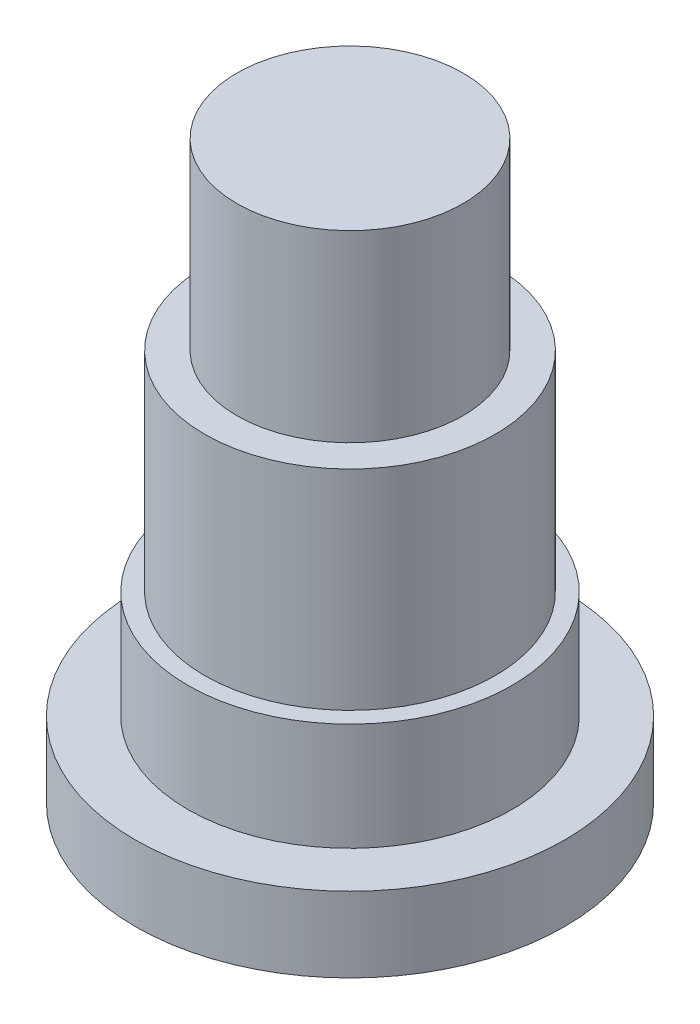
SolidWorks part; units mm, degrees
ref_plane "Plan de face" through (0, 0, 0) normal (0, 0, 1) x (1, 0, 0)
ref_plane "Plan de dessus" through (0, 0, 0) normal (0, 1, 0) x (1, 0, 0)
ref_plane "Plan de droite" through (0, 0, 0) normal (1, 0, 0) x (0, 0, -1)
sketch "Esquisse1" plane through (0, 0, 0) normal (0, 0, 1) x (1, 0, 0)
  line L0 (0, 0) -> (19.865, 0)
  line L1 (0, 0) -> (19.865, 0) construction
  line L2 (0, 0) -> (0, 53.24) construction
  line L3 (0, 53.24) -> (19.865, 53.24) construction
  line L4 (19.865, 0) -> (19.865, 53.24) construction
  line L5 (19.865, 0) -> (19.865, 6.95)
  line L6 (19.865, 6.95) -> (15, 6.95)
  line L7 (15, 6.95) -> (15, 16.9)
  line L8 (15, 16.9) -> (13.44, 16.9)
  line L9 (13.44, 16.9) -> (13.44, 36.24)
  line L10 (13.44, 36.24) -> (10.465, 36.24)
  line L11 (10.465, 36.24) -> (10.465, 53.24)
  line L12 (10.465, 53.24) -> (0, 53.24)
  line L13 (0, 53.24) -> (0, 0)
  dimension "D1" = 19.865
  dimension "D2" = 6.95
  dimension "D3" = 15
  dimension "D4" = 16.9
  dimension "D5" = 13.44
  dimension "D6" = 10.465
  dimension "D7" = 53.24
  dimension "D8" = 17
revolve "Révolution1" add sketch "Esquisse1" angle 360 about L13
